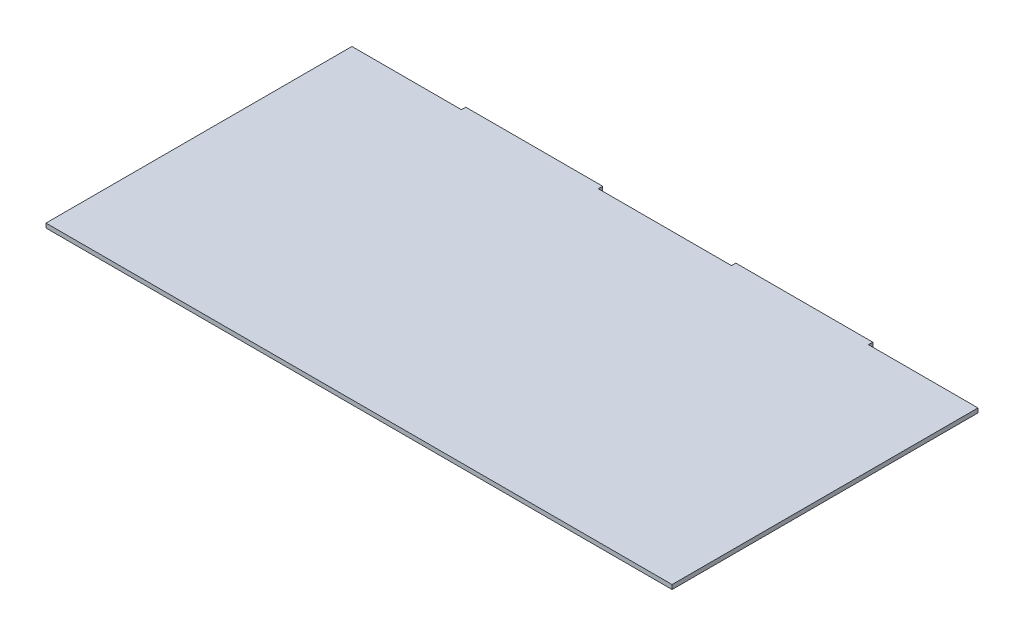
SolidWorks part; units mm, degrees
material "Custom Plastic"
ref_plane "X-Y Datum" through (0, 0, 0) normal (0, 0, 1) x (1, 0, 0)
ref_plane "X-Z Datum" through (0, 0, 0) normal (0, 1, 0) x (1, 0, 0)
ref_plane "Y-Z Datum" through (0, 0, 0) normal (1, 0, 0) x (0, 0, -1)
sketch "Sketch1" plane through (0, 0, 0) normal (0, 0, 1) x (1, 0, 0)
  line L1 (-228.6, -1.5875) -> (228.6, -1.5875)
  line L2 (-228.6, -1.5875) -> (-228.6, 1.5875)
  line L3 (-228.6, 1.5875) -> (228.6, 1.5875)
  line L4 (228.6, -1.5875) -> (228.6, 1.5875)
  line L5 (-228.6, -1.5875) -> (228.6, 1.5875) construction
  line L6 (-228.6, 1.5875) -> (228.6, -1.5875) construction
  point P0 (0, 0)
  dimension "D1" = 3.175
  dimension "D2" = 457.2
extrude "Boss-Extrude1" add sketch "Sketch1" along normal blind 223.38
sketch "Sketch2" plane through (0, 0, 0) normal (0, 0, -1) x (-1, 0, 0)
  line L1 (-148.6, 1.5875) -> (-48.6, 1.5875)
  line L2 (-148.6, 1.5875) -> (-148.6, -1.5875)
  line L3 (-148.6, -1.5875) -> (-48.6, -1.5875)
  line L4 (-48.6, 1.5875) -> (-48.6, -1.5875)
  line L5 (48.623, 1.5875) -> (148.623, 1.5875)
  line L6 (48.623, 1.5875) -> (48.623, -1.5875)
  line L7 (48.623, -1.5875) -> (148.623, -1.5875)
  line L8 (148.623, 1.5875) -> (148.623, -1.5875)
extrude "Boss-Extrude2" add sketch "Sketch2" along normal blind 3.175
